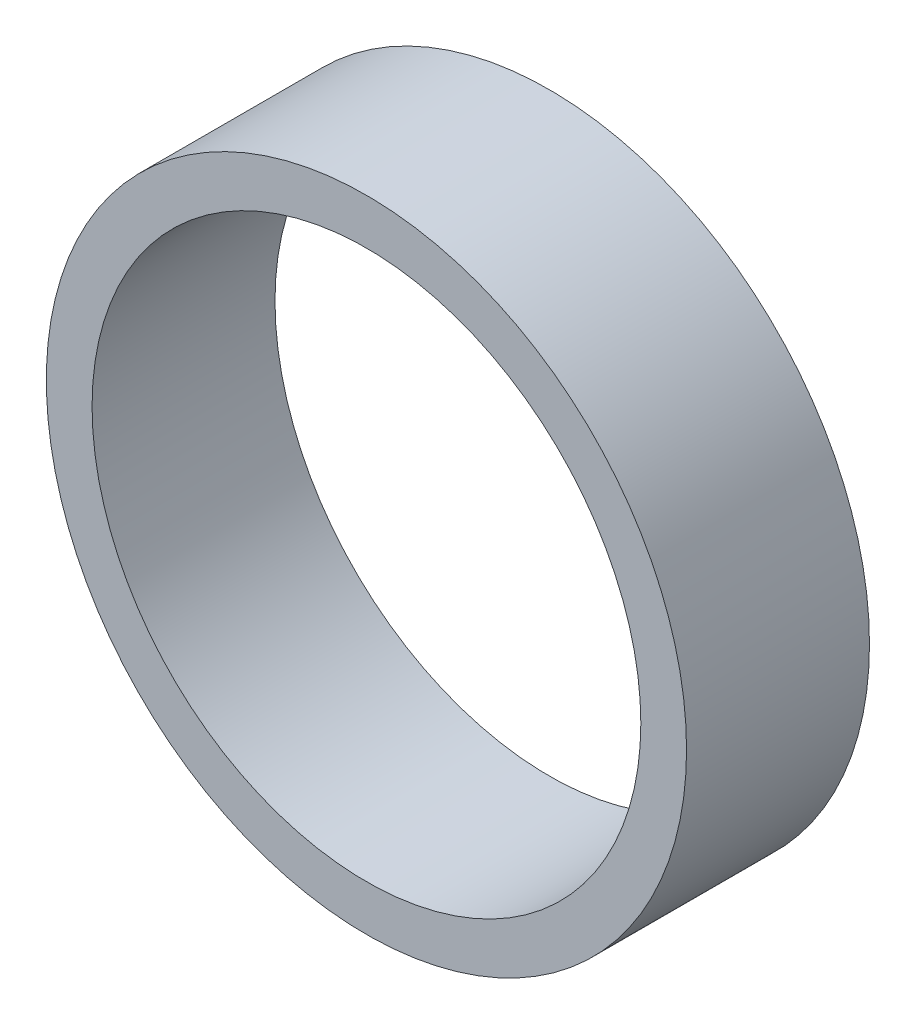
SolidWorks part; units mm, degrees
material "1.0503 (C45)"
ref_plane "Front Plane" through (0, 0, 0) normal (0, 0, 1) x (1, 0, 0)
ref_plane "Top Plane" through (0, 0, 0) normal (0, 1, 0) x (1, 0, 0)
ref_plane "Right Plane" through (0, 0, 0) normal (1, 0, 0) x (0, 0, -1)
sketch "Sketch1" plane through (0, 0, 0) normal (0, 1, 0) x (1, 0, 0)
  line L0 (15, 61) -> (17.5, 61)
  line L1 (17.5, 61) -> (17.5, 71)
  line L2 (17.5, 71) -> (15, 71)
  line L3 (15, 71) -> (15, 61)
  line L4 (0, -150) -> (0, 150) construction
revolve "REV_Cone_Spacer_30x35x10" add sketch "Sketch1" angle 360 about L4
